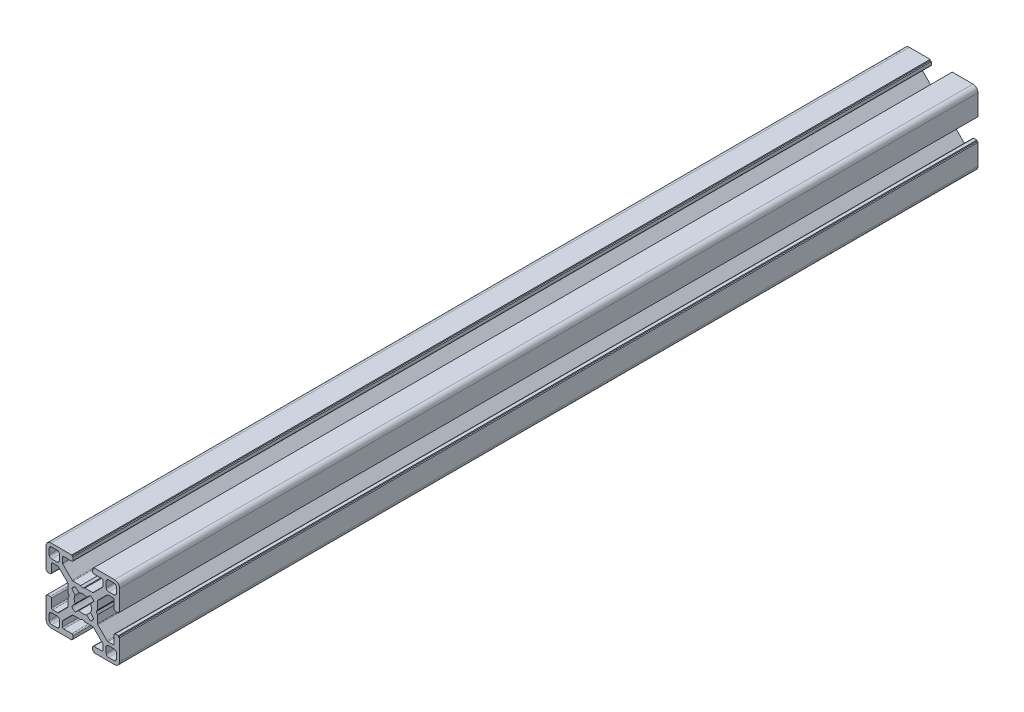
SolidWorks part; units mm, degrees
ref_plane "Front Plane" through (0, 0, 0) normal (0, 0, 1) x (1, 0, 0)
ref_plane "Top Plane" through (0, 0, 0) normal (0, 1, 0) x (1, 0, 0)
ref_plane "Right Plane" through (0, 0, 0) normal (1, 0, 0) x (0, 0, -1)
sketch "Sketch1" plane through (0, 0, 0) normal (0, 0, 1) x (1, 0, 0)
  line L0 (-15, 0) -> (15, 0) construction
  line L1 (0, -15) -> (0, 15) construction
  line L2 (-4.5, 15) -> (4.5, 15) construction
  line L3 (-4, -15) -> (4, -15) construction
  line L4 (-4.5, 15) -> (-4.5, 14.5)
  line L5 (-4.5, 14.5) -> (-4, 14.5)
  line L6 (-4, 14.5) -> (-4, 13.29)
  line L7 (-4.5, 12.79) -> (-7.7675, 12.79)
  line L8 (-8.2675, 12.29) -> (-8.2675, 10.2707)
  line L9 (-8.1211, 9.9171) -> (-4.3504, 6.1464)
  line L10 (-3.9968, 6) -> (0, 6)
  line L11 (0, 0) -> (-15, 15) construction
  line L12 (-4.5, 15) -> (-12.968, 15)
  line L14 (-12.705, 9.5135) -> (-10.5135, 9.5135)
  line L15 (-13.705, 10.5135) -> (-13.705, 12.705)
  line L16 (-12.705, 13.705) -> (-10.5135, 13.705)
  line L17 (-9.5135, 10.5135) -> (-9.5135, 12.705)
  line L18 (-13.705, 9.5135) -> (-9.5135, 13.705) construction
  line L19 (-13.705, 13.705) -> (-9.5135, 9.5135) construction
  line L20 (-3.1568, 4.5038) -> (-1.5303, 3.1477) construction
  line L21 (-4.5038, 3.1568) -> (-3.1477, 1.5303) construction
  line L22 (-6, 3.9968) -> (-6, 0)
  line L23 (-9.9171, 8.1211) -> (-6.1464, 4.3504)
  line L24 (-15, 4.5) -> (-15, 12.968)
  line L25 (-12.29, 8.2675) -> (-10.2707, 8.2675)
  line L26 (-12.79, 4.5) -> (-12.79, 7.7675)
  line L27 (-14.5, 4) -> (-13.29, 4)
  line L28 (-14.5, 4.5) -> (-14.5, 4)
  line L29 (-15, 4.5) -> (-14.5, 4.5)
  circle A0 centre (0, 0) radius 3.5
  arc A1 (-12.968, 15) -> (-15, 12.968) centre (-12.968, 12.968) ccw
  circle A2 centre (0, 0) radius 5.5 construction
  arc A3 (-10.5135, 9.5135) -> (-9.5135, 10.5135) centre (-10.5135, 10.5135) ccw
  arc A4 (-13.705, 12.705) -> (-12.705, 13.705) centre (-12.705, 12.705) cw
  arc A5 (-10.5135, 13.705) -> (-9.5135, 12.705) centre (-10.5135, 12.705) cw
  arc A6 (-12.705, 9.5135) -> (-13.705, 10.5135) centre (-12.705, 10.5135) cw
  arc A7 (-12.79, 4.5) -> (-13.29, 4) centre (-13.29, 4.5) cw
  arc A8 (-12.29, 8.2675) -> (-12.79, 7.7675) centre (-12.29, 7.7675) ccw
  arc A9 (-9.9171, 8.1211) -> (-10.2707, 8.2675) centre (-10.2707, 7.7675) ccw
  arc A10 (-6, 3.9968) -> (-6.1464, 4.3504) centre (-6.5, 3.9968) ccw
  arc A11 (-4.3504, 6.1464) -> (-3.9968, 6) centre (-3.9968, 6.5) ccw
  arc A12 (-4, 13.29) -> (-4.5, 12.79) centre (-4.5, 13.29) cw
  arc A13 (-7.7675, 12.79) -> (-8.2675, 12.29) centre (-7.7675, 12.29) ccw
  arc A14 (-8.2675, 10.2707) -> (-8.1211, 9.9171) centre (-7.7675, 10.2707) ccw
  point P4 (0, 0)
  point P8 (0, 0)
  point P13 (0, 15)
  point P15 (0, -15)
  point P16 (0, 6)
  point P23 (-11.6092, 11.6093)
  point P26 (0, 6)
  point P62 (-12.79, 4)
  point P65 (-12.79, 8.2675)
  point P68 (-10.0636, 8.2675)
  point P71 (-6, 4.2039)
  point P74 (-4.2039, 6)
  point P77 (-4, 12.79)
  point P80 (-8.2675, 12.79)
  point P83 (-8.2675, 10.0636)
  dimension "Center Hole Diameter" = 7
  dimension "D11" = 2.032
  dimension "D9" = 11
  dimension "D13" = 1
  dimension "D14" = 0.5
  dimension "Rail Height" = 30
  dimension "Rail Width" = 30
  dimension "T-Slot Width" = 8
  dimension "T-Slot Depth" = 9
  dimension "D1" = 9
  dimension "D2" = 45
  dimension "D3" = 8
  dimension "D4" = 2.21
  dimension "D5" = 16.535
  dimension "D7" = 2.54
  dimension "D6" = 1.295
  dimension "D8" = 1.246
  dimension "D10" = 10.36
  dimension "D12" = 1.905
sketch "Sketch2" plane through (0, 0, 0) normal (1, 0, 0) x (0, 0, -1)
  line L0 (-76.2, 0) -> (76.2, 0) construction
  line L2 (0, -15) -> (0, 15) construction
  line L3 (0, -15) -> (0, 15) construction
  line L4 (-76.2, -15) -> (-76.2, 15) construction
  line L5 (76.2, -15) -> (76.2, 15) construction
  point P0 (-38.7, 0)
  point P3 (0, 0)
  point P4 (38.7, 0)
  point P12 (-76.2, 0)
  point P14 (76.2, 0)
  dimension "Length" = 152.4
  dimension "D1" = 37.5
sketch "Sketch3" plane through (0, 0, 0) normal (0, 0, 1) x (1, 0, 0)
  line L0 (-4.5038, 3.1568) -> (-3.1477, 1.5303)
  line L1 (0, 3.5) -> (0, 5.5)
  line L2 (-5.5, 0) -> (-3.5, 0)
  line L7 (-6, 3.9968) -> (-6, 0) construction
  line L31 (-9.9171, 8.1211) -> (-6.1464, 4.3504) construction
  line L117 (-12.29, 8.2675) -> (-10.2707, 8.2675) construction
  line L118 (-12.79, 4.5) -> (-12.79, 7.7675) construction
  line L157 (-12.705, 9.5135) -> (-10.5135, 9.5135)
  line L158 (-9.5135, 10.5135) -> (-9.5135, 12.705)
  line L163 (-10.5135, 13.705) -> (-12.705, 13.705)
  line L164 (-13.705, 12.705) -> (-13.705, 10.5135)
  line L165 (-12.705, 9.5135) -> (-10.5135, 9.5135)
  line L166 (-9.5135, 10.5135) -> (-9.5135, 12.705)
  line L167 (-10.5135, 13.705) -> (-12.705, 13.705)
  line L168 (-13.705, 12.705) -> (-13.705, 10.5135)
  line L169 (-14.5, 4) -> (-13.29, 4) construction
  line L170 (-14.5, 4.5) -> (-14.5, 4) construction
  line L171 (-15, 4.5) -> (-14.5, 4.5) construction
  line L172 (-15, 4.5) -> (-15, 12.968) construction
  line L173 (-4.5, 15) -> (-12.968, 15) construction
  line L174 (-4.5, 15) -> (-4.5, 14.5) construction
  line L175 (-4.5, 14.5) -> (-4, 14.5) construction
  line L176 (-4, 14.5) -> (-4, 13.29) construction
  line L177 (-4.5, 12.79) -> (-7.7675, 12.79) construction
  line L178 (-8.2675, 12.29) -> (-8.2675, 10.2707) construction
  line L179 (-8.1211, 9.9171) -> (-4.3504, 6.1464) construction
  line L180 (-3.9968, 6) -> (0, 6) construction
  line L181 (-6, 3.9968) -> (-6, 0.866)
  line L182 (-9.9171, 8.1211) -> (-6.1464, 4.3504)
  line L183 (-12.29, 8.2675) -> (-10.2707, 8.2675)
  line L184 (-12.79, 4.5) -> (-12.79, 7.7675)
  line L185 (-14.5, 4) -> (-13.29, 4)
  line L186 (-14.5, 4.5) -> (-14.5, 4)
  line L187 (-15, 4.5) -> (-14.5, 4.5)
  line L188 (-15, 4.5) -> (-15, 12.968)
  line L189 (-4.5, 15) -> (-12.968, 15)
  line L190 (-4.5, 15) -> (-4.5, 14.5)
  line L191 (-4.5, 14.5) -> (-4, 14.5)
  line L192 (-4, 14.5) -> (-4, 13.29)
  line L193 (-4.5, 12.79) -> (-7.7675, 12.79)
  line L194 (-8.2675, 12.29) -> (-8.2675, 10.2707)
  line L195 (-8.1211, 9.9171) -> (-4.3504, 6.1464)
  line L196 (-3.9968, 6) -> (-0.866, 6)
  line L197 (-0.866, 6) -> (0, 5.5)
  line L198 (0, -15) -> (0, 15) construction
  line L199 (0, 0) -> (-15, 15) construction
  line L200 (0, 0) -> (-15, 15) construction
  line L201 (-3.1568, 4.5038) -> (-1.5303, 3.1477) construction
  line L202 (-3.1568, 4.5038) -> (-1.5303, 3.1477)
  line L203 (-6, 0.866) -> (-5.5, 0)
  line L204 (-15, 0) -> (15, 0) construction
  line L205 (-15, 0) -> (15, 0) construction
  line L206 (0, -15) -> (0, 15) construction
  arc A0 (-3.5, 0) -> (-3.1477, 1.5303) centre (0, 0) cw
  arc A10 (-6, 3.9968) -> (-6.1464, 4.3504) centre (-6.5, 3.9968) ccw construction
  circle A16 centre (0, 0) radius 3.5
  arc A18 (0, 3.5) -> (-1.5303, 3.1477) centre (0, 0) ccw
  arc A20 (-9.9171, 8.1211) -> (-10.2707, 8.2675) centre (-10.2707, 7.7675) ccw construction
  arc A22 (-12.29, 8.2675) -> (-12.79, 7.7675) centre (-12.29, 7.7675) ccw construction
  arc A28 (-13.29, 4) -> (-12.79, 4.5) centre (-13.29, 4.5) ccw construction
  arc A29 (-10.5135, 9.5135) -> (-9.5135, 10.5135) centre (-10.5135, 10.5135) ccw
  arc A30 (-9.5135, 12.705) -> (-10.5135, 13.705) centre (-10.5135, 12.705) ccw
  arc A31 (-12.705, 13.705) -> (-13.705, 12.705) centre (-12.705, 12.705) ccw
  arc A32 (-13.705, 10.5135) -> (-12.705, 9.5135) centre (-12.705, 10.5135) ccw
  arc A33 (-10.5135, 9.5135) -> (-9.5135, 10.5135) centre (-10.5135, 10.5135) ccw
  arc A34 (-9.5135, 12.705) -> (-10.5135, 13.705) centre (-10.5135, 12.705) ccw
  arc A35 (-12.705, 13.705) -> (-13.705, 12.705) centre (-12.705, 12.705) ccw
  arc A36 (-13.705, 10.5135) -> (-12.705, 9.5135) centre (-12.705, 10.5135) ccw
  arc A37 (-12.968, 15) -> (-15, 12.968) centre (-12.968, 12.968) ccw construction
  arc A38 (-4.5, 12.79) -> (-4, 13.29) centre (-4.5, 13.29) ccw construction
  arc A39 (-7.7675, 12.79) -> (-8.2675, 12.29) centre (-7.7675, 12.29) ccw construction
  arc A40 (-8.2675, 10.2707) -> (-8.1211, 9.9171) centre (-7.7675, 10.2707) ccw construction
  arc A41 (-4.3504, 6.1464) -> (-3.9968, 6) centre (-3.9968, 6.5) ccw construction
  arc A42 (-6, 3.9968) -> (-6.1464, 4.3504) centre (-6.5, 3.9968) ccw
  arc A43 (-9.9171, 8.1211) -> (-10.2707, 8.2675) centre (-10.2707, 7.7675) ccw
  arc A44 (-12.29, 8.2675) -> (-12.79, 7.7675) centre (-12.29, 7.7675) ccw
  arc A45 (-13.29, 4) -> (-12.79, 4.5) centre (-13.29, 4.5) ccw
  arc A46 (-12.968, 15) -> (-15, 12.968) centre (-12.968, 12.968) ccw
  arc A47 (-4.5, 12.79) -> (-4, 13.29) centre (-4.5, 13.29) ccw
  arc A48 (-7.7675, 12.79) -> (-8.2675, 12.29) centre (-7.7675, 12.29) ccw
  arc A49 (-8.2675, 10.2707) -> (-8.1211, 9.9171) centre (-7.7675, 10.2707) ccw
  arc A50 (-4.3504, 6.1464) -> (-3.9968, 6) centre (-3.9968, 6.5) ccw
  circle A51 centre (0, 0) radius 5.5 construction
  arc A52 (-3.1568, 4.5038) -> (-4.5038, 3.1568) centre (0, 0) ccw
  dimension "D3" = 60
  dimension "D4" = 60
  dimension "D1" = 0
  dimension "D2" = 0
extrude "Boss-Extrude1" add sketch "Sketch3" along normal mid plane 350
pattern_circular "CirPattern1" count 4 over 360 about axis through (0, 0, 0) along (0, 0, 1) of "Boss-Extrude1"
ref_plane "Contact Plane1" through (15, 0, 0) normal (1, 0, 0) x (0, 0, -1)
ref_plane "Contact Plane2" through (0, -15, 0) normal (0, 1, 0) x (1, 0, 0)
ref_plane "Contact Plane3" through (-15, 0, 0) normal (1, 0, 0) x (0, 0, -1)
ref_plane "Contact Plane4" through (0, 15, 0) normal (0, 1, 0) x (1, 0, 0)
equation "\"D1@Sketch2\" = \"Rail Height@Sketch1\" * 1.25"
equation "\"D1@Sketch1\"=\"T-Slot Width@Sketch1\"+1mm"
equation "\"D3@Sketch1\"=\"T-Slot Width@Sketch1\""
equation "\"D1@Boss-Extrude1\"=\"length\""
equation "\"length\" = 350"
